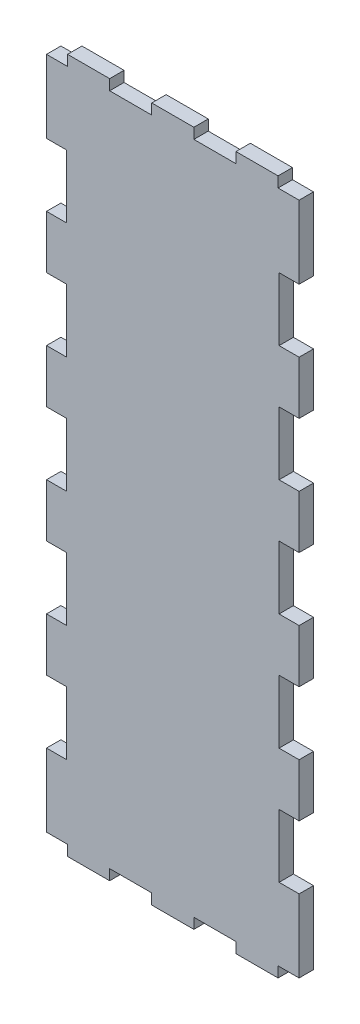
SolidWorks part; units mm, degrees
ref_plane "Front Plane" through (0, 0, 0) normal (0, 0, 1) x (1, 0, 0)
ref_plane "Top Plane" through (0, 0, 0) normal (0, 1, 0) x (1, 0, 0)
ref_plane "Right Plane" through (0, 0, 0) normal (1, 0, 0) x (0, 0, -1)
sketch "Sketch1" plane through (0, 0, 0) normal (0, 0, 1) x (1, 0, 0)
  line L1 (-38.1, -101.6) -> (38.1, -101.6)
  line L2 (-38.1, -101.6) -> (-38.1, 101.6)
  line L3 (-38.1, 101.6) -> (38.1, 101.6)
  line L4 (38.1, -101.6) -> (38.1, 101.6)
  line L5 (-38.1, -101.6) -> (38.1, 101.6) construction
  line L6 (-38.1, 101.6) -> (38.1, -101.6) construction
  point P0 (0, 0)
  dimension "D1" = 203.2
  dimension "D2" = 76.2
extrude "Boss-Extrude1" add sketch "Sketch1" along normal blind 4.3434
sketch "Sketch2" plane through (0, 0, 4.3434) normal (0, 0, 1) x (1, 0, 0)
  line L0 (38.1, 101.6) -> (-38.1, 101.6) construction
  line L1 (-6.35, 98.425) -> (6.35, 98.425)
  line L2 (-6.35, 98.425) -> (-6.35, 104.775)
  line L3 (-6.35, 104.775) -> (6.35, 104.775)
  line L4 (6.35, 98.425) -> (6.35, 104.775)
  line L5 (-6.35, 98.425) -> (6.35, 104.775) construction
  line L6 (-6.35, 104.775) -> (6.35, 98.425) construction
  line L7 (-31.75, 104.775) -> (-19.05, 104.775)
  line L8 (-19.05, 98.425) -> (-19.05, 104.775)
  line L9 (-31.75, 98.425) -> (-19.05, 98.425)
  line L10 (-31.75, 98.425) -> (-31.75, 104.775)
  line L11 (0, 101.6) -> (0, 0) construction
  line L12 (31.75, 98.425) -> (31.75, 104.775)
  line L13 (31.75, 98.425) -> (19.05, 98.425)
  line L14 (19.05, 98.425) -> (19.05, 104.775)
  line L15 (31.75, 104.775) -> (19.05, 104.775)
  line L16 (0, 0) -> (38.1, 0) construction
  line L17 (38.1, -101.6) -> (38.1, 101.6) construction
  line L18 (-6.35, -104.775) -> (6.35, -98.425) construction
  line L19 (-6.35, -98.425) -> (6.35, -104.775) construction
  line L20 (31.75, -104.775) -> (19.05, -104.775)
  line L21 (19.05, -98.425) -> (19.05, -104.775)
  line L22 (31.75, -98.425) -> (19.05, -98.425)
  line L23 (31.75, -98.425) -> (31.75, -104.775)
  line L24 (-31.75, -98.425) -> (-31.75, -104.775)
  line L25 (-31.75, -98.425) -> (-19.05, -98.425)
  line L26 (-19.05, -98.425) -> (-19.05, -104.775)
  line L27 (-31.75, -104.775) -> (-19.05, -104.775)
  line L28 (6.35, -98.425) -> (6.35, -104.775)
  line L29 (-6.35, -104.775) -> (6.35, -104.775)
  line L30 (-6.35, -98.425) -> (-6.35, -104.775)
  line L31 (-6.35, -98.425) -> (6.35, -98.425)
  point P0 (0, 101.6)
  point P33 (0, -101.6)
  dimension "D1" = 12.7
  dimension "D2" = 6.35
  dimension "D3" = 2
extrude "Boss-Extrude2" add sketch "Sketch2" against normal up to surface (4.3434 mm away) up to face at (0, 0, 0)
sketch "Sketch3" plane through (0, 0, 4.3434) normal (0, 0, 1) x (1, 0, 0)
  line L0 (38.1, -101.6) -> (38.1, 101.6) construction
  line L1 (32.0548, -9.525) -> (44.1452, -9.525)
  line L2 (32.0548, -9.525) -> (32.0548, 9.525)
  line L3 (32.0548, 9.525) -> (44.1452, 9.525)
  line L4 (44.1452, -9.525) -> (44.1452, 9.525)
  line L5 (32.0548, -9.525) -> (44.1452, 9.525) construction
  line L6 (32.0548, 9.525) -> (44.1452, -9.525) construction
  line L7 (32.0548, 25.527) -> (44.1452, 25.527)
  line L8 (44.1452, 25.527) -> (44.1452, 44.577)
  line L9 (32.0548, 44.577) -> (44.1452, 44.577)
  line L10 (32.0548, 25.527) -> (32.0548, 44.577)
  line L11 (32.0548, 60.579) -> (44.1452, 60.579)
  line L12 (44.1452, 60.579) -> (44.1452, 79.629)
  line L13 (32.0548, 79.629) -> (44.1452, 79.629)
  line L14 (32.0548, 60.579) -> (32.0548, 79.629)
  line L15 (0, 0) -> (-38.1, 0) construction
  line L16 (-38.1, 101.6) -> (-38.1, -101.6) construction
  line L17 (32.0548, -60.579) -> (32.0548, -79.629)
  line L18 (32.0548, -79.629) -> (44.1452, -79.629)
  line L19 (44.1452, -60.579) -> (44.1452, -79.629)
  line L20 (32.0548, -60.579) -> (44.1452, -60.579)
  line L21 (32.0548, -25.527) -> (32.0548, -44.577)
  line L22 (32.0548, -44.577) -> (44.1452, -44.577)
  line L23 (44.1452, -25.527) -> (44.1452, -44.577)
  line L24 (32.0548, -25.527) -> (44.1452, -25.527)
  line L25 (0, 104.775) -> (0, 0) construction
  line L26 (6.35, 104.775) -> (-6.35, 104.775) construction
  line L27 (-32.0548, 9.525) -> (-44.1452, -9.525) construction
  line L28 (-32.0548, -9.525) -> (-44.1452, 9.525) construction
  line L29 (-32.0548, -25.527) -> (-44.1452, -25.527)
  line L30 (-44.1452, -25.527) -> (-44.1452, -44.577)
  line L31 (-32.0548, -44.577) -> (-44.1452, -44.577)
  line L32 (-32.0548, -25.527) -> (-32.0548, -44.577)
  line L33 (-32.0548, -60.579) -> (-44.1452, -60.579)
  line L34 (-44.1452, -60.579) -> (-44.1452, -79.629)
  line L35 (-32.0548, -79.629) -> (-44.1452, -79.629)
  line L36 (-32.0548, -60.579) -> (-32.0548, -79.629)
  line L37 (-32.0548, 60.579) -> (-32.0548, 79.629)
  line L38 (-32.0548, 79.629) -> (-44.1452, 79.629)
  line L39 (-44.1452, 60.579) -> (-44.1452, 79.629)
  line L40 (-32.0548, 60.579) -> (-44.1452, 60.579)
  line L41 (-32.0548, 25.527) -> (-32.0548, 44.577)
  line L42 (-32.0548, 44.577) -> (-44.1452, 44.577)
  line L43 (-44.1452, 25.527) -> (-44.1452, 44.577)
  line L44 (-32.0548, 25.527) -> (-44.1452, 25.527)
  line L45 (-44.1452, -9.525) -> (-44.1452, 9.525)
  line L46 (-32.0548, 9.525) -> (-44.1452, 9.525)
  line L47 (-32.0548, -9.525) -> (-32.0548, 9.525)
  line L48 (-32.0548, -9.525) -> (-44.1452, -9.525)
  point P0 (38.1, 0)
  dimension "D1" = 19.05
  dimension "D2" = 12.0904
  dimension "D3" = 3
extrude "Cut-Extrude1" cut sketch "Sketch3" against normal through all
